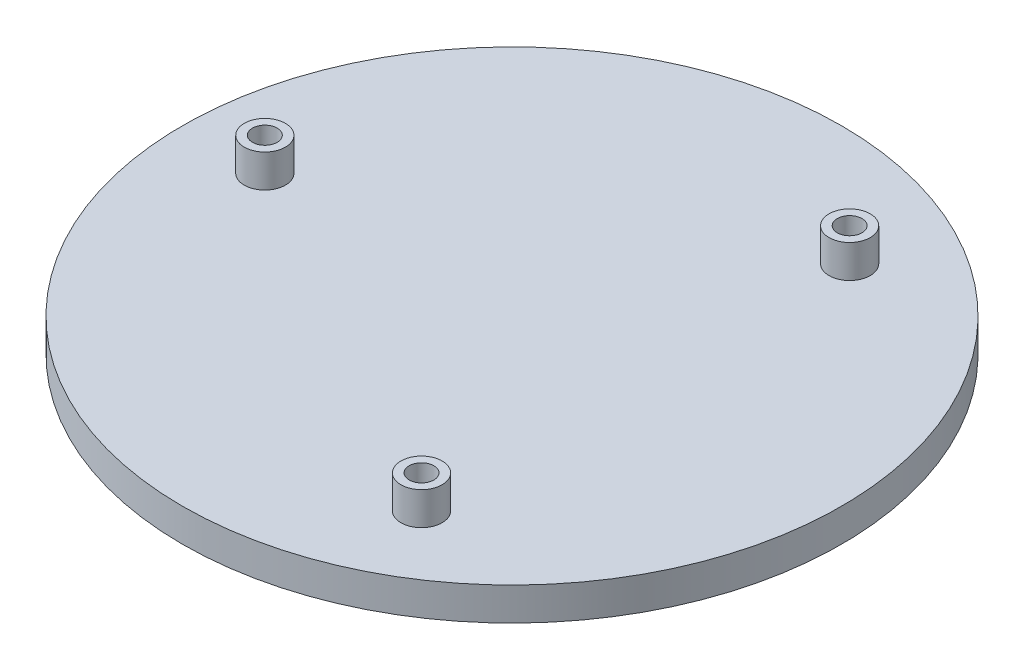
SolidWorks part; units mm, degrees
ref_plane "Front Plane" through (0, 0, 0) normal (0, 0, 1) x (1, 0, 0)
ref_plane "Top Plane" through (0, 0, 0) normal (0, 1, 0) x (1, 0, 0)
ref_plane "Right Plane" through (0, 0, 0) normal (1, 0, 0) x (0, 0, -1)
sketch "Sketch1" plane through (0, 0, 0) normal (0, 0, 1) x (1, 0, 0)
  line L0 (0, 0) -> (-50.8, 0)
  line L1 (-50.8, 0) -> (-50.8, -5.08)
  line L2 (-50.8, -5.08) -> (-38.1, -5.08)
  line L3 (-38.1, -5.08) -> (-38.1, -2.54)
  line L4 (-38.1, -2.54) -> (0, -2.54)
  line L5 (0, -2.54) -> (0, 0)
  dimension "D1" = 50.8
  dimension "D2" = 12.7
  dimension "D3" = 5.08
  dimension "D4" = 2.54
sketch "Sketch2" plane through (0, 0, 0) normal (0, 0, 1) x (1, 0, 0)
  line L0 (0, 4.5677) -> (0, -8.0056) construction
revolve "Revolve1" add sketch "Sketch1" angle 360 about L0
sketch "Sketch3" plane through (0, 0, 0) normal (0, 1, 0) x (1, 0, 0)
  circle A0 centre (-38.1, 0) radius 3.175
  circle A1 centre (-38.1, 0) radius 1.905
  circle A2 centre (0, 0) radius 50.8 construction
  circle A3 centre (19.05, 32.9956) radius 3.175
  circle A4 centre (19.05, 32.9956) radius 1.905
  circle A5 centre (19.05, -32.9956) radius 3.175
  circle A6 centre (19.05, -32.9956) radius 1.905
  point P14 (0, 0)
  dimension "D2" = 6.35
  dimension "D3" = 3.81
  dimension "D1" = 38.1
  dimension "D4" = 3
extrude "Boss-Extrude1" add sketch "Sketch3" along normal blind 5.08
